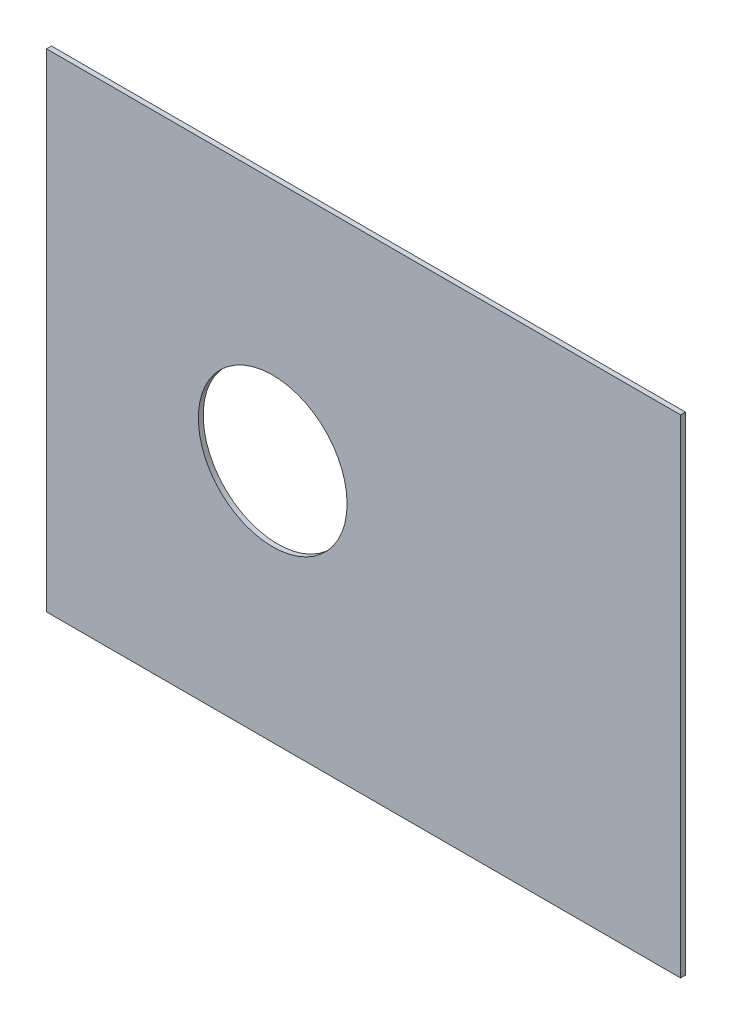
SolidWorks part; units mm, degrees
ref_plane "Спереди" through (0, 0, 0) normal (0, 0, 1) x (1, 0, 0)
ref_plane "Сверху" through (0, 0, 0) normal (0, 1, 0) x (1, 0, 0)
ref_plane "Справа" through (0, 0, 0) normal (1, 0, 0) x (0, 0, -1)
other "Configuration Table"
sketch "Эскиз1" plane through (0, 0, 0) normal (0, 0, 1) x (1, 0, 0)
  line L1 (130, 100) -> (-130, 100)
  line L2 (130, 100) -> (130, -100)
  line L3 (130, -100) -> (-130, -100)
  line L4 (-130, 100) -> (-130, -100)
  line L5 (130, 100) -> (-130, -100) construction
  line L6 (130, -100) -> (-130, 100) construction
  circle A0 centre (-37.26, 0) radius 30.5
  point P0 (0, 0)
  dimension "D3" = 61
  dimension "D1" = 260
  dimension "D2" = 200
  dimension "D4" = 92.74
extrude "Бобышка-Вытянуть1" add sketch "Эскиз1" along normal blind 2
sketch "Эскиз2" plane through (0, 0, 0) normal (0, 0, -1) x (-1, 0, 0)
  line L0 (-130, 100) -> (130, 100) construction
  line L5 (-130, -100) -> (-130, 100) construction
  line L6 (-130, 25) -> (19.7886, 25)
  line L7 (-130, 25) -> (-130, -25)
  line L8 (-130, -25) -> (19.7886, -25)
  line L9 (19.7886, 25) -> (19.7886, -25)
  line L10 (12.26, 100) -> (62.26, 100)
  line L11 (12.26, 100) -> (12.26, 17.4714)
  line L12 (12.26, 17.4714) -> (62.26, 17.4714) construction
  line L13 (62.26, 100) -> (62.26, 17.4714)
  line L14 (6.76, 0) -> (67.76, 0) construction
  line L15 (37.26, 30.5) -> (37.26, -30.5) construction
  line L16 (12.26, -100) -> (62.26, -100)
  line L17 (62.26, -100) -> (62.26, -17.4714)
  line L18 (12.26, -100) -> (12.26, -17.4714)
  line L19 (130, 100) -> (130, -100) construction
  line L20 (54.7314, 25) -> (130, 25)
  line L21 (54.7314, 25) -> (54.7314, -25)
  line L22 (54.7314, -25) -> (130, -25)
  line L23 (130, 25) -> (130, -25)
  circle A0 centre (37.26, 0) radius 30.5
  circle A1 centre (37.26, 0) radius 30.5 construction
  point P9 (-130, 0)
  point P17 (37.26, 100)
  point P32 (130, 0)
  line M12 (130, -100) -> (130, 100)
  line M13 (130, 100) -> (-130, 100)
  line M14 (-130, 100) -> (-130, -100)
  line M15 (-130, -100) -> (130, -100)
  circle M16 centre (37.26, 0) radius 30.5
  dimension "D1" = 50
  dimension "D3" = 50
  dimension "D2" = 50
extrude "Бобышка-Вытянуть5" [suppressed] add sketch "Эскиз2" along normal blind 50 contours L18 L8 M16 | L22 L17 M16 | L20 L13 M16 | L6 L11 M16 | L20 L13 L11 L6 M16 M13 | L8 L18 L11 L6 M16 M14 | L22 L8 L18 L17 M16 M15 | L17 L22 L20 L13 M12 M16
equation "\"D3@Эскиз2\"=\"D1@Эскиз2\""
equation "\"D2@Эскиз2\"=\"D1@Эскиз2\""
